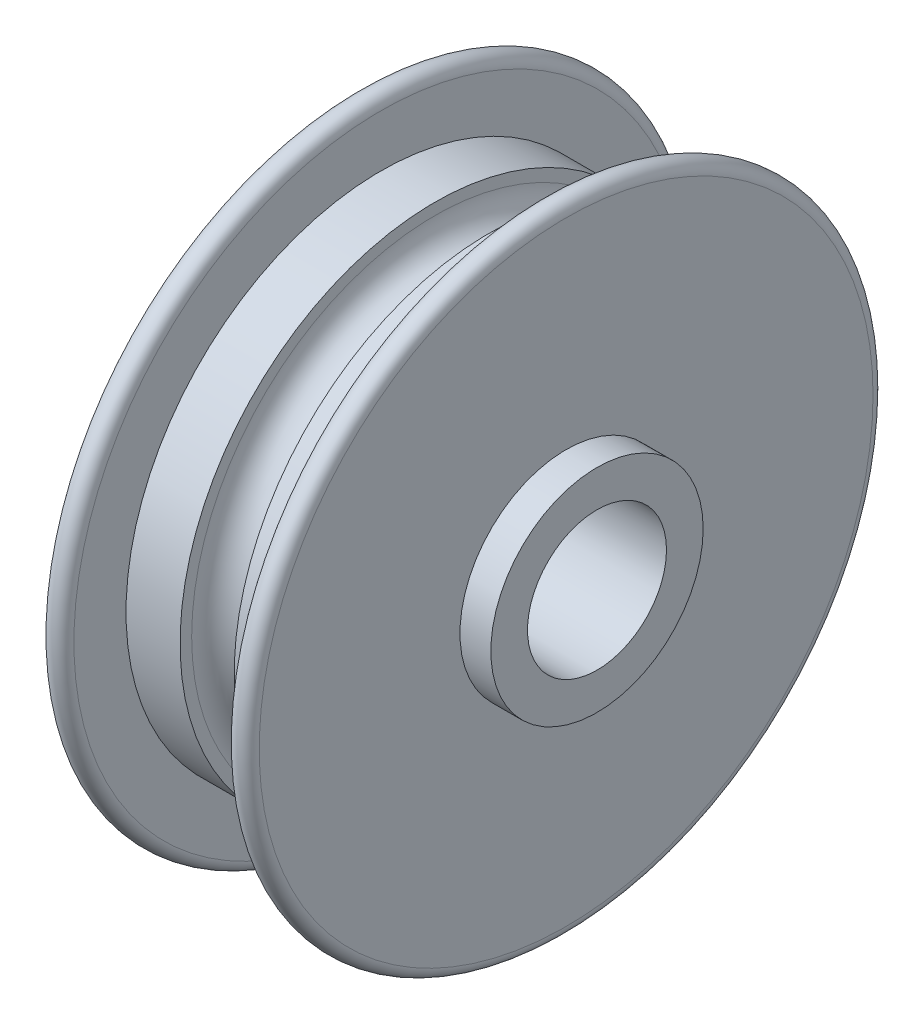
SolidWorks part; units mm, degrees
ref_plane "Front Plane" through (0, 0, 0) normal (0, 0, 1) x (1, 0, 0)
ref_plane "Top Plane" through (0, 0, 0) normal (0, 1, 0) x (1, 0, 0)
ref_plane "Right Plane" through (0, 0, 0) normal (1, 0, 0) x (0, 0, -1)
sketch "Sketch1" plane through (0, 0, 0) normal (0, 0, 1) x (1, 0, 0)
  line L0 (-24.4616, 0) -> (40.6384, 0) construction
  line L1 (26.1759, 13.75) -> (26.1759, 9)
  line L2 (26.1759, 13.75) -> (22.1759, 13.75)
  line L3 (22.1759, 13.75) -> (22.1759, 39.75)
  line L4 (19.1759, 39.75) -> (19.1759, 33)
  line L6 (8.6759, 28) -> (8.6759, 9)
  line L7 (-8.8241, 9) -> (26.1759, 9)
  line L8 (-8.8241, 13.75) -> (-4.8241, 13.75)
  line L9 (-4.8241, 13.75) -> (-4.8241, 39.75)
  line L10 (-1.8241, 39.75) -> (-1.8241, 33)
  line L12 (-8.8241, 13.75) -> (-8.8241, 9)
  line L13 (8.6759, 31.5) -> (14.6934, 31.5) construction
  line L15 (12.1759, 31.5) -> (12.1759, 33)
  line L16 (12.1759, 33) -> (19.1759, 33)
  line L17 (8.6759, 31.5) -> (0.8815, 31.5) construction
  line L18 (-1.8241, 33) -> (5.1759, 33)
  line L19 (5.1759, 33) -> (5.1759, 31.5)
  arc A0 (22.1759, 39.75) -> (19.1759, 39.75) centre (20.6759, 39.75) ccw
  arc A1 (5.1759, 31.5) -> (12.1759, 31.5) centre (8.6759, 31.5) ccw
  arc A2 (-4.8241, 39.75) -> (-1.8241, 39.75) centre (-3.3241, 39.75) cw
  dimension "D1" = 1.5
  dimension "D4" = 3.5
  dimension "D2" = 13.5
  dimension "D3" = 17.5
  dimension "D5" = 13.75
  dimension "D6" = 9
  dimension "D7" = 31.5
  dimension "D9" = 39.75
revolve "Revolve1" add sketch "Sketch1" angle 360 about L0
